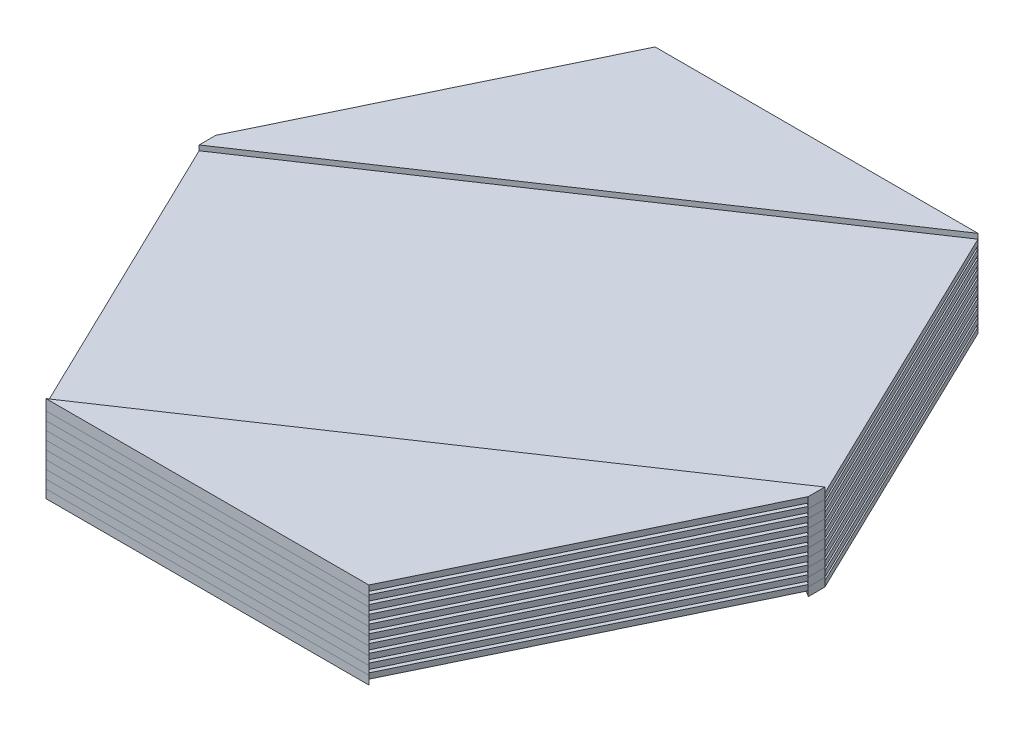
SolidWorks part; units mm, degrees
ref_plane "Front Plane" through (0, 0, 0) normal (0, 0, 1) x (1, 0, 0)
ref_plane "Top Plane" through (0, 0, 0) normal (0, 1, 0) x (1, 0, 0)
ref_plane "Right Plane" through (0, 0, 0) normal (1, 0, 0) x (0, 0, -1)
sketch "Sketch1" plane through (0, 0, 0) normal (0, 1, 0) x (1, 0, 0)
  line L0 (-97, 183) -> (-183, 5)
  line L1 (-97, 183) -> (97, 183)
  line L2 (-97, 183) -> (-97, -183) construction
  line L3 (-97, -183) -> (97, -183)
  line L4 (97, 183) -> (97, -183) construction
  line L5 (-97, 183) -> (97, -183) construction
  line L6 (-97, -183) -> (97, 183) construction
  line L7 (-183, -5) -> (-97, -183)
  line L8 (97, 183) -> (183, 5)
  line L9 (183, -5) -> (97, -183)
  line L10 (183, 0) -> (-183, 0) construction
  line L12 (183, 5) -> (183, -5)
  line L13 (-183, 5) -> (-183, -5)
  point P0 (0, 0)
  point P5 (183, 0)
  point P6 (-183, 0)
  dimension "D1" = 194
  dimension "D2" = 366
  dimension "D3" = 10
  dimension "D4" = 366
extrude "Boss-Extrude1" add sketch "Sketch1" along normal blind 6.35
sketch "Sketch2" plane through (0, 6.35, 0) normal (0, 1, 0) x (1, 0, 0)
  line L0 (-183, -5) -> (97, 183)
  line L1 (97, 183) -> (183, 5)
  line L2 (183, 5) -> (-97, -183)
  line L3 (-97, -183) -> (-183, -5)
  line L5 (183, 5) -> (97, 183) construction
  line L9 (-183, -5) -> (-97, -183) construction
extrude "Cut-Extrude1" cut sketch "Sketch2" against normal blind 3.048
sketch "Sketch3" plane through (0, 0, 0) normal (0, -1, 0) x (1, 0, 0)
  line L0 (183, 5) -> (-97, -183)
  line L1 (-97, -183) -> (-183, -5)
  line L2 (-183, -5) -> (97, 183)
  line L4 (97, 183) -> (183, 5)
extrude "Cut-Extrude2" cut sketch "Sketch3" against normal blind 3.048
pattern_linear "LPattern2" count 10 spacing 5.08 along (0, 1, 0) of bodies 103
